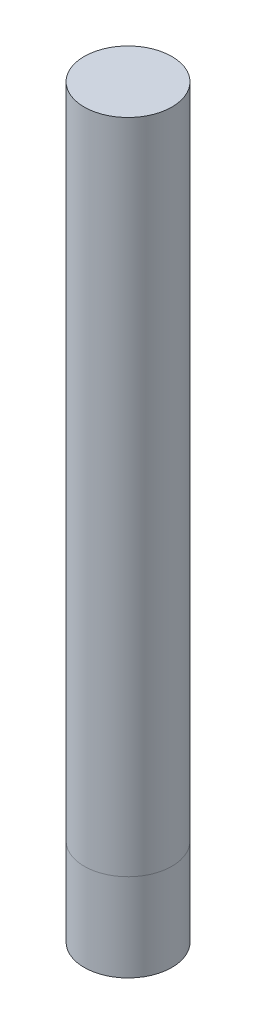
SolidWorks part; units mm, degrees
ref_plane "Přední rovina" through (0, 0, 0) normal (0, 0, 1) x (1, 0, 0)
ref_plane "Horní rovina" through (0, 0, 0) normal (0, 1, 0) x (1, 0, 0)
ref_plane "Pravá rovina" through (0, 0, 0) normal (1, 0, 0) x (0, 0, -1)
sketch "Skica1" plane through (0, 0, 0) normal (0, 1, 0) x (1, 0, 0)
  circle A0 centre (0, 0) radius 4
  dimension "D1" = 8
extrude "Přidat vysunutím1" add sketch "Skica1" along normal blind 68
sketch "Skica2" plane through (0, 0, 0) normal (0, -1, 0) x (1, 0, 0)
  circle A0 centre (0, 0) radius 4
  circle A1 centre (0, 0) radius 3.999
  circle A2 centre (0, 0) radius 4 construction
  dimension "D1" = 0.001
extrude "Odebrat vysunutím1" cut sketch "Skica2" against normal blind 8
